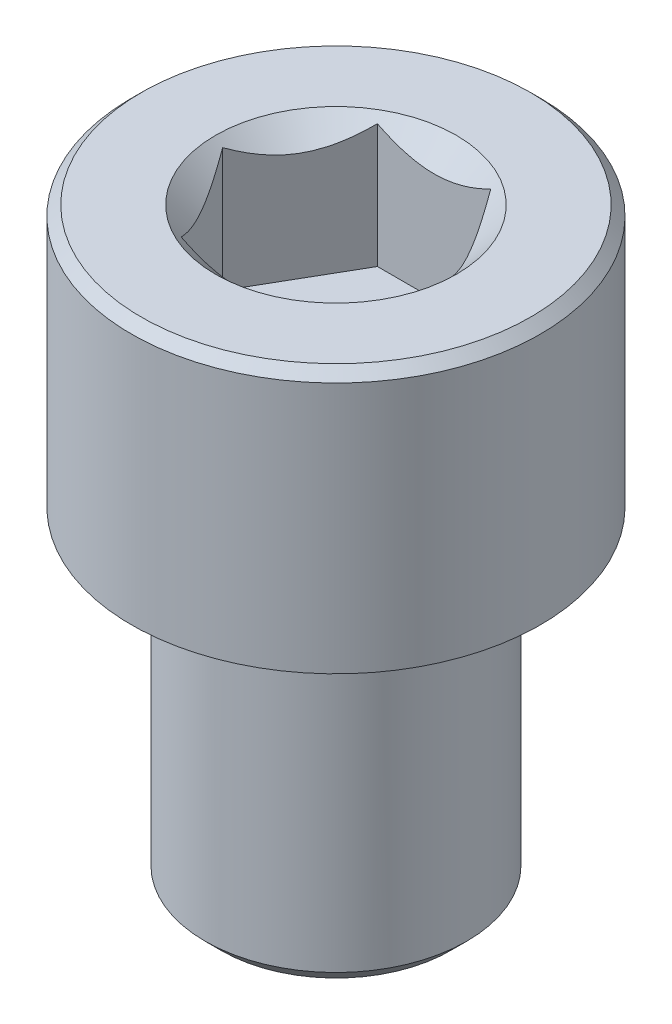
SolidWorks part; units mm, degrees
ref_plane "Płaszczyzna przednia" through (0, 0, 0) normal (0, 0, 1) x (1, 0, 0)
ref_plane "Płaszczyzna górna" through (0, 0, 0) normal (0, 1, 0) x (1, 0, 0)
ref_plane "Płaszczyzna prawa" through (0, 0, 0) normal (1, 0, 0) x (0, 0, -1)
sketch "Szkic1" plane through (0, 0, 0) normal (0, 0, 1) x (1, 0, 0)
  line L0 (0, 0) -> (0, 67.7826) construction
  line L1 (0, 0) -> (-4, 0)
  line L2 (-4, 0) -> (-4, 10)
  line L3 (-4, 10) -> (-6.25, 10)
  line L4 (-6.25, 10) -> (-6.25, 18)
  line L5 (-6.25, 18) -> (0, 18)
  line L6 (0, 18) -> (0, 0)
  dimension "D1" = 12.5
  dimension "D2" = 8
  dimension "D3" = 8
  dimension "D4" = 10
revolve "Obrót1" add sketch "Szkic1" angle 360 about L0
cosmetic thread "Oznaczenie gwintu1" parameters "D2"=6.619
sketch "Szkic2" plane through (0, 18, 0) normal (0, 1, 0) x (1, 0, 0)
  line L0 (0, 0) -> (5.3969, 0) construction
  line L1 (3.4641, 0) -> (1.7321, 3)
  line L2 (1.7321, 3) -> (-1.7321, 3)
  line L3 (-1.7321, 3) -> (-3.4641, 0)
  line L4 (-3.4641, 0) -> (-1.7321, -3)
  line L5 (-1.7321, -3) -> (1.7321, -3)
  line L6 (1.7321, -3) -> (3.4641, 0)
  circle A0 centre (0, 0) radius 3 construction
  dimension "D1" = 6
extrude "Wyciągnięcie1" cut sketch "Szkic2" against normal blind 4
chamfer "Sfazowanie1" distance 0.3 angle 45 1 edges at (0, 18, -6.25)
sketch "Szkic3" plane through (0, 18, 0) normal (0, 1, 0) x (1, 0, 0)
  circle A0 centre (0, 0) radius 3.6817
extrude "Wytnij-wyciągnięcie1" cut sketch "Szkic3" against normal blind 2 draft 45
chamfer "Sfazowanie2" distance 0.5 angle 45 1 edges at (0, 0, -4)
